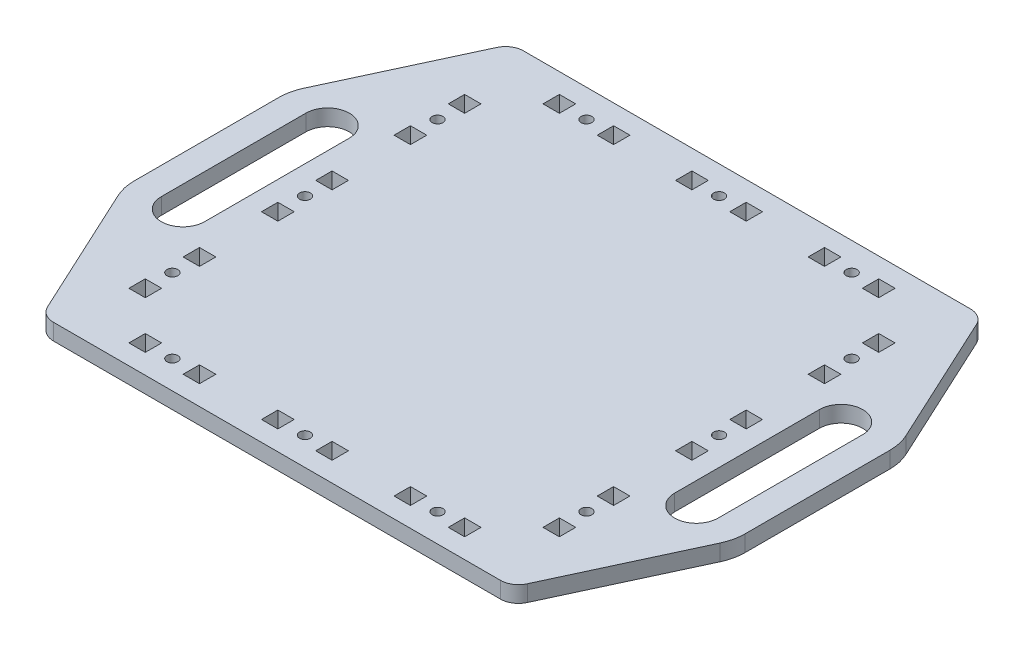
SolidWorks part; units mm, degrees
ref_plane "Front Plane" through (0, 0, 0) normal (0, 0, 1) x (1, 0, 0)
ref_plane "Top Plane" through (0, 0, 0) normal (0, 1, 0) x (1, 0, 0)
ref_plane "Right Plane" through (0, 0, 0) normal (1, 0, 0) x (0, 0, -1)
sketch "Sketch1" plane through (0, 0, 0) normal (0, 1, 0) x (1, 0, 0)
  line L0 (142, 40) -> (142, -40) construction
  line L1 (-110, -110) -> (110, -110) construction
  line L2 (-110, -110) -> (-110, 110) construction
  line L3 (-110, 110) -> (110, 110) construction
  line L4 (110, -110) -> (110, 110) construction
  line L5 (-110, -110) -> (110, 110) construction
  line L6 (-110, 110) -> (110, -110) construction
  line L7 (-123.6163, -130) -> (123.6163, -130)
  line L9 (-123.6163, 130) -> (123.6163, 130)
  line L11 (-130, -130) -> (130, 130) construction
  line L12 (-130, 130) -> (130, -130) construction
  line L13 (154, 40) -> (154, -40)
  line L14 (130, 40) -> (130, -40)
  line L15 (0, 0) -> (331.9652, 0) construction
  line L16 (0, 0) -> (0, 229.8832) construction
  line L17 (169, 40) -> (169, -40)
  line L18 (166.4913, -51.3655) -> (132.6872, -124.2094)
  line L19 (166.4913, 51.3655) -> (132.6872, 124.2094)
  line L20 (-142, 40) -> (-142, -40) construction
  line L21 (-154, 40) -> (-154, -40)
  line L22 (-130, 40) -> (-130, -40)
  line L23 (-166.4913, -51.3655) -> (-132.6872, -124.2094)
  line L24 (-169, 40) -> (-169, -40)
  line L25 (-166.4913, 51.3655) -> (-132.6872, 124.2094)
  arc A0 (154, 40) -> (130, 40) centre (142, 40) ccw
  arc A1 (130, -40) -> (154, -40) centre (142, -40) ccw
  arc A2 (169, 40) -> (166.4913, 51.3655) centre (142, 40) ccw
  arc A3 (169, -40) -> (166.4913, -51.3655) centre (142, -40) cw
  arc A4 (-154, 40) -> (-130, 40) centre (-142, 40) cw
  arc A5 (-130, -40) -> (-154, -40) centre (-142, -40) cw
  arc A6 (-169, -40) -> (-166.4913, -51.3655) centre (-142, -40) ccw
  arc A7 (-169, 40) -> (-166.4913, 51.3655) centre (-142, 40) cw
  arc A8 (-123.6163, -130) -> (-132.6872, -124.2094) centre (-123.6163, -120) cw
  arc A9 (132.6872, -124.2094) -> (123.6163, -130) centre (123.6163, -120) cw
  arc A10 (132.6872, 124.2094) -> (123.6163, 130) centre (123.6163, 120) ccw
  arc A11 (-123.6163, 130) -> (-132.6872, 124.2094) centre (-123.6163, 120) ccw
  point P0 (0, 0)
  point P6 (0, 0)
  point P13 (142, 0)
  point P31 (-142, 0)
  point P55 (0, 0)
  line B0 (19.525, 119.05) -> (10.475, 119.05)
  line B1 (-19.525, 110) -> (-10.475, 110)
  line B2 (-19.525, 110) -> (-19.525, 119.05)
  line B3 (-19.525, 119.05) -> (-10.475, 119.05)
  line B4 (-10.475, 110) -> (-10.475, 119.05)
  line B5 (10.475, 110) -> (10.475, 119.05)
  line B6 (19.525, 110) -> (10.475, 110)
  line B7 (19.525, 110) -> (19.525, 119.05)
  circle B8 centre (0, 114.525) radius 3
  line B9 (-73.3333, 119.9951) -> (-73.3333, 109.5131) construction
  line B10 (-53.8083, 119.05) -> (-62.8583, 119.05)
  line B11 (-92.8583, 110) -> (-83.8083, 110)
  line B12 (-92.8583, 110) -> (-92.8583, 119.05)
  line B13 (-92.8583, 119.05) -> (-83.8083, 119.05)
  line B14 (-83.8083, 110) -> (-83.8083, 119.05)
  line B15 (-62.8583, 110) -> (-62.8583, 119.05)
  line B16 (-53.8083, 110) -> (-62.8583, 110)
  line B17 (-53.8083, 110) -> (-53.8083, 119.05)
  circle B18 centre (-73.3333, 114.525) radius 3
  line B19 (73.3333, 119.9951) -> (73.3333, 109.5131) construction
  line B20 (92.8583, 119.05) -> (83.8083, 119.05)
  line B21 (53.8083, 110) -> (62.8583, 110)
  line B22 (53.8083, 110) -> (53.8083, 119.05)
  line B23 (53.8083, 119.05) -> (62.8583, 119.05)
  line B24 (62.8583, 110) -> (62.8583, 119.05)
  line B25 (83.8083, 110) -> (83.8083, 119.05)
  line B26 (92.8583, 110) -> (83.8083, 110)
  line B27 (92.8583, 110) -> (92.8583, 119.05)
  circle B28 centre (73.3333, 114.525) radius 3
  line B29 (119.05, 53.8083) -> (119.05, 62.8583)
  line B30 (110, 92.8583) -> (110, 83.8083)
  line B31 (110, 92.8583) -> (119.05, 92.8583)
  line B32 (119.05, 92.8583) -> (119.05, 83.8083)
  line B33 (110, 83.8083) -> (119.05, 83.8083)
  line B34 (110, 62.8583) -> (119.05, 62.8583)
  line B35 (110, 53.8083) -> (110, 62.8583)
  line B36 (110, 53.8083) -> (119.05, 53.8083)
  circle B37 centre (114.525, 73.3333) radius 3
  line B38 (119.05, -19.525) -> (119.05, -10.475)
  line B39 (110, 19.525) -> (110, 10.475)
  line B40 (110, 19.525) -> (119.05, 19.525)
  line B41 (119.05, 19.525) -> (119.05, 10.475)
  line B42 (110, 10.475) -> (119.05, 10.475)
  line B43 (110, -10.475) -> (119.05, -10.475)
  line B44 (110, -19.525) -> (110, -10.475)
  line B45 (110, -19.525) -> (119.05, -19.525)
  circle B46 centre (114.525, 0) radius 3
  line B47 (119.05, -92.8583) -> (119.05, -83.8083)
  line B48 (110, -53.8083) -> (110, -62.8583)
  line B49 (110, -53.8083) -> (119.05, -53.8083)
  line B50 (119.05, -53.8083) -> (119.05, -62.8583)
  line B51 (110, -62.8583) -> (119.05, -62.8583)
  line B52 (110, -83.8083) -> (119.05, -83.8083)
  line B53 (110, -92.8583) -> (110, -83.8083)
  line B54 (110, -92.8583) -> (119.05, -92.8583)
  circle B55 centre (114.525, -73.3333) radius 3
  line B56 (53.8083, -119.05) -> (62.8583, -119.05)
  line B57 (92.8583, -110) -> (83.8083, -110)
  line B58 (92.8583, -110) -> (92.8583, -119.05)
  line B59 (92.8583, -119.05) -> (83.8083, -119.05)
  line B60 (83.8083, -110) -> (83.8083, -119.05)
  line B61 (62.8583, -110) -> (62.8583, -119.05)
  line B62 (53.8083, -110) -> (62.8583, -110)
  line B63 (53.8083, -110) -> (53.8083, -119.05)
  circle B64 centre (73.3333, -114.525) radius 3
  line B65 (-19.525, -119.05) -> (-10.475, -119.05)
  line B66 (19.525, -110) -> (10.475, -110)
  line B67 (19.525, -110) -> (19.525, -119.05)
  line B68 (19.525, -119.05) -> (10.475, -119.05)
  line B69 (10.475, -110) -> (10.475, -119.05)
  line B70 (-10.475, -110) -> (-10.475, -119.05)
  line B71 (-19.525, -110) -> (-10.475, -110)
  line B72 (-19.525, -110) -> (-19.525, -119.05)
  circle B73 centre (0, -114.525) radius 3
  line B74 (-92.8583, -119.05) -> (-83.8083, -119.05)
  line B75 (-53.8083, -110) -> (-62.8583, -110)
  line B76 (-53.8083, -110) -> (-53.8083, -119.05)
  line B77 (-53.8083, -119.05) -> (-62.8583, -119.05)
  line B78 (-62.8583, -110) -> (-62.8583, -119.05)
  line B79 (-83.8083, -110) -> (-83.8083, -119.05)
  line B80 (-92.8583, -110) -> (-83.8083, -110)
  line B81 (-92.8583, -110) -> (-92.8583, -119.05)
  circle B82 centre (-73.3333, -114.525) radius 3
  line B83 (-119.05, -53.8083) -> (-119.05, -62.8583)
  line B84 (-110, -92.8583) -> (-110, -83.8083)
  line B85 (-110, -92.8583) -> (-119.05, -92.8583)
  line B86 (-119.05, -92.8583) -> (-119.05, -83.8083)
  line B87 (-110, -83.8083) -> (-119.05, -83.8083)
  line B88 (-110, -62.8583) -> (-119.05, -62.8583)
  line B89 (-110, -53.8083) -> (-110, -62.8583)
  line B90 (-110, -53.8083) -> (-119.05, -53.8083)
  circle B91 centre (-114.525, -73.3333) radius 3
  line B92 (-119.05, 19.525) -> (-119.05, 10.475)
  line B93 (-110, -19.525) -> (-110, -10.475)
  line B94 (-110, -19.525) -> (-119.05, -19.525)
  line B95 (-119.05, -19.525) -> (-119.05, -10.475)
  line B96 (-110, -10.475) -> (-119.05, -10.475)
  line B97 (-110, 10.475) -> (-119.05, 10.475)
  line B98 (-110, 19.525) -> (-110, 10.475)
  line B99 (-110, 19.525) -> (-119.05, 19.525)
  circle B100 centre (-114.525, 0) radius 3
  line B101 (-119.05, 92.8583) -> (-119.05, 83.8083)
  line B102 (-110, 53.8083) -> (-110, 62.8583)
  line B103 (-110, 53.8083) -> (-119.05, 53.8083)
  line B104 (-119.05, 53.8083) -> (-119.05, 62.8583)
  line B105 (-110, 62.8583) -> (-119.05, 62.8583)
  line B106 (-110, 83.8083) -> (-119.05, 83.8083)
  line B107 (-110, 92.8583) -> (-110, 83.8083)
  line B108 (-110, 92.8583) -> (-119.05, 92.8583)
  circle B109 centre (-114.525, 73.3333) radius 3
sketch_block_instance "Insert_9mm_M6_bois-1"
sketch_block "Insert_9mm_M6_bois" parameters "D4"=6, "D1"=9.05, "D2"=9.05, "D3"=15
sketch_block_instance "Insert_9mm_M6_bois-2"
sketch_block_instance "Insert_9mm_M6_bois-3"
sketch_block_instance "Insert_9mm_M6_bois-5"
sketch_block_instance "Insert_9mm_M6_bois-6"
sketch_block_instance "Insert_9mm_M6_bois-7"
sketch_block_instance "Insert_9mm_M6_bois-8"
sketch_block_instance "Insert_9mm_M6_bois-9"
sketch_block_instance "Insert_9mm_M6_bois-10"
sketch_block_instance "Insert_9mm_M6_bois-11"
sketch_block_instance "Insert_9mm_M6_bois-12"
sketch_block_instance "Insert_9mm_M6_bois-13" parameters "D5"=122.84, "D8"=10, "D1"=20.9221, "D2"=222.3152, "D3"=220, "D4"=90, "D6"=77.8446, "D7"=80, "D9"=331.9652, "D10"=90.3287, "D11"=36.7488
extrude "Boss-Extrude1" add sketch "Sketch1" along normal blind 9
